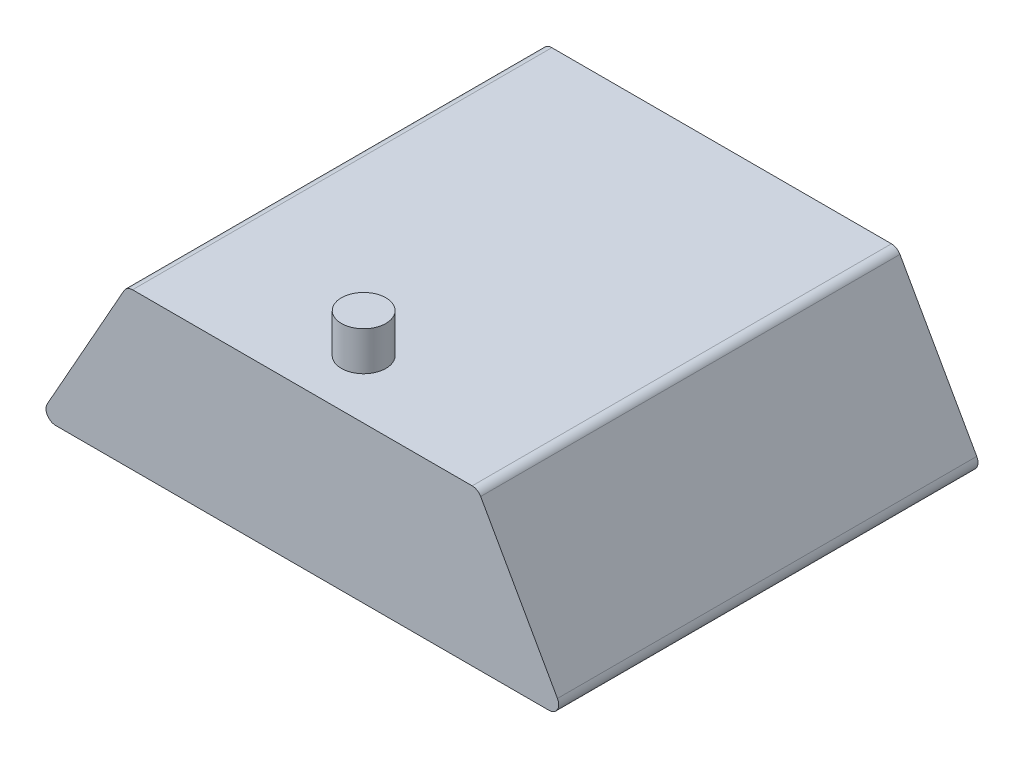
SolidWorks part; units mm, degrees
ref_plane "前基準面" through (0, 0, 0) normal (0, 0, 1) x (1, 0, 0)
ref_plane "上基準面" through (0, 0, 0) normal (0, 1, 0) x (1, 0, 0)
ref_plane "右基準面" through (0, 0, 0) normal (1, 0, 0) x (0, 0, -1)
sketch "草圖1" plane through (0, 0, 0) normal (0, 0, 1) x (1, 0, 0)
  line L0 (-130.8086, -66.7692) -> (-91.4336, 3.2308)
  line L1 (-126.4508, -74.2205) -> (126.4508, -74.2205)
  line L5 (-87.0758, 5.7795) -> (87.0758, 5.7795)
  line L6 (91.4336, 3.2308) -> (130.8086, -66.7692)
  line L7 (0, 5.7795) -> (0, -74.2205) construction
  arc A0 (-126.4508, -74.2205) -> (-130.8086, -66.7692) centre (-126.4508, -69.2205) cw
  arc A1 (126.4508, -74.2205) -> (130.8086, -66.7692) centre (126.4508, -69.2205) ccw
  arc A2 (91.4336, 3.2308) -> (87.0758, 5.7795) centre (87.0758, 0.7795) ccw
  arc A3 (-91.4336, 3.2308) -> (-87.0758, 5.7795) centre (-87.0758, 0.7795) cw
  point P0 (0, 0)
  point P10 (-135, -74.2205)
  point P13 (135, -74.2205)
  point P16 (90, 5.7795)
  point P19 (-90, 5.7795)
  dimension "D6" = 5
  dimension "D1" = 270
  dimension "D2" = 180
  dimension "D3" = 80
  dimension "D4" = 135
  dimension "D5" = 0
extrude "填料-伸長1" add sketch "草圖1" along normal blind 215 contours L5 A2 L6 A1 L1 A0 L0 A3
sketch "草圖2" plane through (0, -74.2205, 0) normal (0, -1, 0) x (1, 0, 0)
  line L0 (0, 215) -> (0, 143.3672) construction
  line L1 (-126.4508, 215) -> (126.4508, 215) construction
  line L2 (-135, 107.5) -> (-42.8148, 107.5) construction
  line L3 (-135, 215) -> (-135, 0) construction
  circle A0 centre (-100, 185.9897) radius 12.5
  circle A1 centre (-100, 29.0103) radius 12.5
  circle A2 centre (100, 29.0103) radius 12.5
  circle A3 centre (100, 185.9897) radius 12.5
  dimension "D2" = 25
  dimension "D1" = 100
extrude "填料-伸長2" add sketch "草圖2" along normal blind 10 draft 15
sketch "Sketch1" plane through (0, 5.7795, 0) normal (0, 1, 0) x (1, 0, 0)
  line L2 (91.4336, -215) -> (91.4336, 0) construction
  line L4 (-87.0758, 0) -> (87.0758, 0) construction
  circle A0 centre (1.4336, -185) radius 11.4044
  point P6 (44.325, -215)
  dimension "D1" = 90
  dimension "D2" = 185
extrude "Boss-Extrude1" add sketch "Sketch1" along normal blind 20
